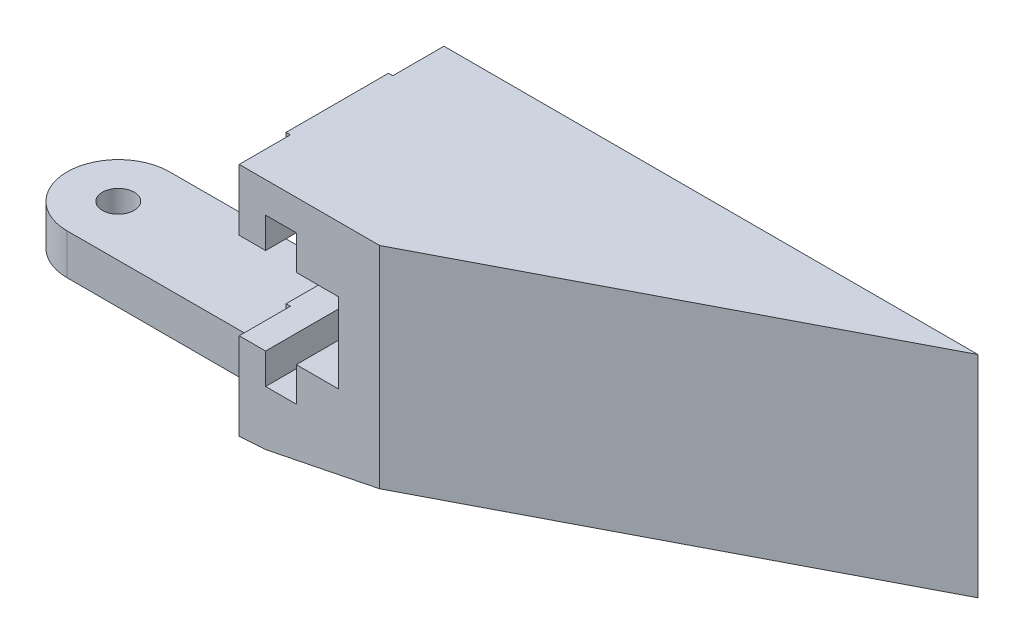
SolidWorks part; units mm, degrees
ref_plane "前视基准面" through (0, 0, 0) normal (0, 0, 1) x (1, 0, 0)
ref_plane "上视基准面" through (0, 0, 0) normal (0, 1, 0) x (1, 0, 0)
ref_plane "右视基准面" through (0, 0, 0) normal (1, 0, 0) x (0, 0, -1)
sketch "草图1" plane through (0, 0, 0) normal (0, 0, 1) x (1, 0, 0)
  line L0 (-13.1003, 11.5) -> (39.49, 11.5)
  line L1 (39.49, 11.5) -> (39.49, -9.0832)
  line L2 (39.49, -9.0832) -> (1.0443, -9.0832)
  line L3 (1.0443, -9.0832) -> (-7.4163, -10.7953)
  line L4 (-10.024, -11.323) -> (-12.6787, -11.5)
  line L5 (-12.6787, -11.5) -> (-39.49, -11.5)
  line L6 (-39.49, -11.5) -> (-39.49, -7.5361)
  line L7 (-39.49, -7.5361) -> (-13.1003, -7.5)
  line L8 (-13.1003, -7.5) -> (-13.1003, -3)
  line L9 (-13.1003, -3) -> (-10.1003, -3)
  line L10 (-10.1003, -3) -> (-10.1003, -6)
  line L11 (-10.1003, -6) -> (-7.1003, -6)
  line L12 (-7.1003, -6) -> (-7.1003, -2.65)
  line L13 (-7.1003, -2.65) -> (-3.0003, -2.65)
  line L14 (-3.0003, -2.65) -> (-3.0003, 5.15)
  line L15 (-3.0003, 5.15) -> (-7.1003, 5.15)
  line L16 (-7.1003, 5.15) -> (-7.1003, 8.5)
  line L17 (-7.1003, 8.5) -> (-10.1003, 8.5)
  line L18 (-10.1003, 8.5) -> (-10.1003, 5.5)
  line L19 (-10.1003, 5.5) -> (-13.1003, 5.5)
  line L20 (-13.1003, 5.5) -> (-13.1003, 11.5)
  line L21 (-10.024, -11.323) -> (-7.4163, -10.7953)
extrude "凸台-拉伸1" add sketch "草图1" along normal blind 20
sketch "草图2" plane through (0, -9.0832, 0) normal (0, -1, 0) x (1, 0, 0)
  line L0 (1.0443, 20) -> (39.49, 0)
  line L1 (39.49, 0) -> (39.49, 20)
  line L2 (39.49, 20) -> (1.0443, 20)
extrude "切除-拉伸1" cut sketch "草图2" against normal through all both and the other way through all
sketch "草图3" plane through (0, -11.5, 0) normal (0, -1, 0) x (1, 0, 0)
  line L0 (-12.6787, 20) -> (-12.6787, 15)
  line L1 (-12.6787, 20) -> (-12.6787, 0) construction
  line L2 (-12.6787, 15) -> (-39.49, 15)
  line L3 (-39.49, 20) -> (-39.49, 0) construction
  line L4 (-39.49, 15) -> (-39.49, 20)
  line L5 (-39.49, 20) -> (-12.6787, 20)
  line L7 (-39.49, 5) -> (-12.6787, 5)
  line L8 (-12.6787, 5) -> (-12.6787, 0)
  line L9 (-12.6787, 0) -> (-39.49, 0)
  line L10 (-39.49, 0) -> (-39.49, 5)
extrude "切除-拉伸2" cut sketch "草图3" against normal through all both and the other way through all
sketch "草图4" plane through (0, -11.5, 0) normal (0, -1, 0) x (1, 0, 0)
  line L0 (-34.49, 15) -> (-39.49, 15)
  line L1 (-12.6787, 15) -> (-39.49, 15) construction
  line L2 (-39.49, 15) -> (-39.49, 5)
  line L3 (-39.49, 5) -> (-12.6787, 5) construction
  line L4 (-39.49, 15) -> (-39.49, 5) construction
  line L5 (-39.49, 5) -> (-34.49, 5)
  arc A0 (-34.49, 5) -> (-39.49, 10) centre (-34.49, 10) cw
  arc A1 (-39.49, 10) -> (-34.49, 15) centre (-34.49, 10) cw
  line M2 (-12.6787, 15) -> (-39.49, 15)
  line M3 (-39.49, 15) -> (-39.49, 5)
  line M4 (-39.49, 5) -> (-12.6787, 5)
extrude "切除-拉伸3" cut sketch "草图4" against normal through all both and the other way through all contours A1 M3 M2 | A0 L2 M4
sketch "草图5" plane through (0, -11.5, 0) normal (0, -1, 0) x (1, 0, 0)
  circle A0 centre (-34.49, 10) radius 1.55
extrude "切除-拉伸4" cut sketch "草图5" against normal through all both and the other way through all
